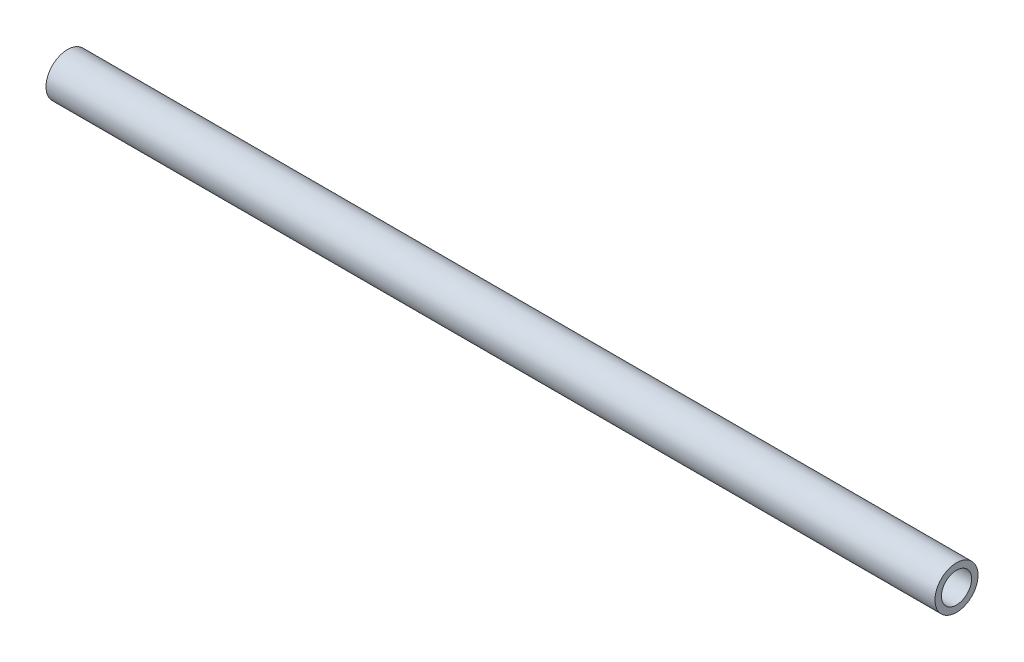
SolidWorks part; units mm, degrees
ref_plane "Plano frontal" through (0, 0, 0) normal (0, 0, 1) x (1, 0, 0)
ref_plane "Plano superior" through (0, 0, 0) normal (0, 1, 0) x (1, 0, 0)
ref_plane "Plano direito" through (0, 0, 0) normal (1, 0, 0) x (0, 0, -1)
sketch "Esboço1" plane through (0, 0, 0) normal (0, 0, 1) x (1, 0, 0)
  line L0 (0, 0) -> (94.9685, 0) construction
  line L2 (0, 2.2) -> (90.8, 2.2)
  line L3 (0, 2.2) -> (0, 1.54)
  line L4 (0, 1.54) -> (90.8, 1.54)
  line L5 (90.8, 2.2) -> (90.8, 1.54)
  dimension "D1" = 4.4
  dimension "D2" = 3.08
  dimension "D3" = 90.8
revolve "Revolução1" add sketch "Esboço1" angle 360 about L0
sketch "Esboço2" plane through (0, 0, 0) normal (0, 1, 0) x (1, 0, 0)
  line L0 (90.8, 0) -> (0, 0) construction
  line L1 (90.8, -1.54) -> (90.8, 1.54) construction
  line L2 (0, 1.54) -> (0, -1.54) construction
  circle A0 centre (45.4, 0) radius 2.5
  dimension "D1" = 5
